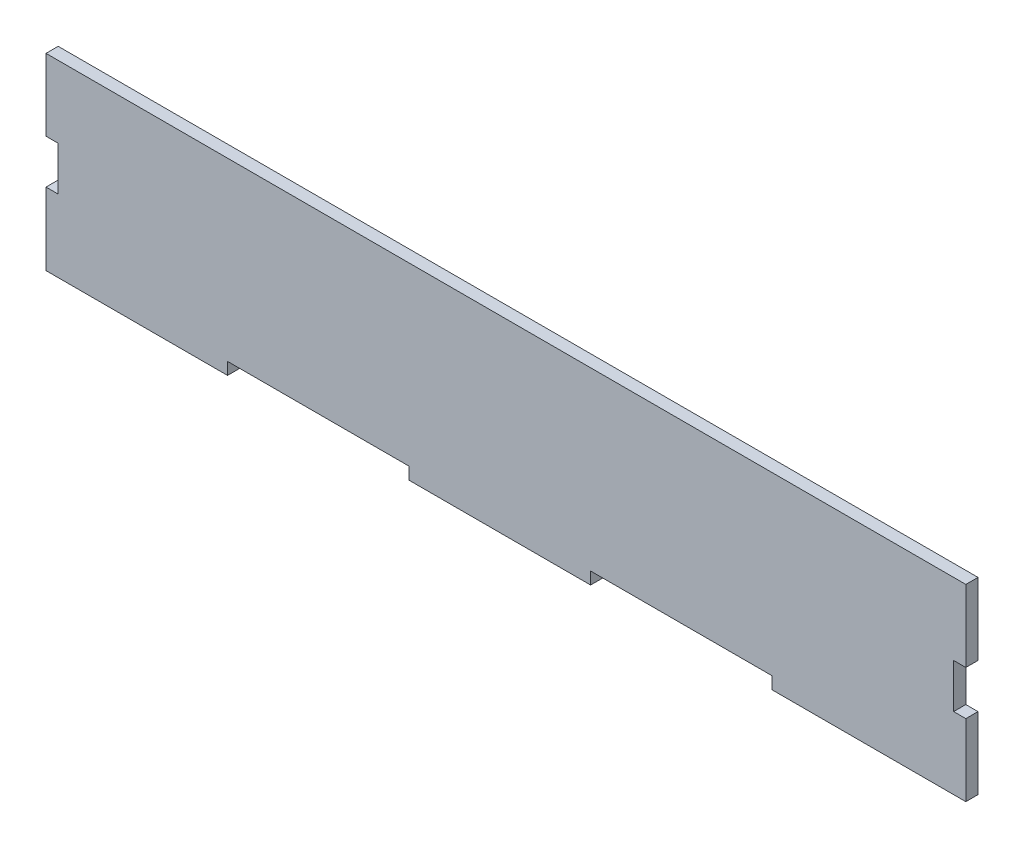
SolidWorks part; units mm, degrees
ref_plane "Alzado" through (0, 0, 0) normal (0, 0, 1) x (1, 0, 0)
ref_plane "Planta" through (0, 0, 0) normal (0, 1, 0) x (1, 0, 0)
ref_plane "Vista lateral" through (0, 0, 0) normal (1, 0, 0) x (0, 0, -1)
sketch "Croquis1" plane through (0, 0, 0) normal (0, 0, 1) x (1, 0, 0)
  line L0 (-48.5339, 1.4205) -> (-48.5339, 33.8414)
  line L1 (-48.5339, 33.8414) -> (366.9661, 33.8414)
  line L2 (-48.5339, -18.4689) -> (-48.5339, -51.1586)
  line L3 (-48.5339, -51.1586) -> (33.4661, -51.1586)
  line L4 (366.9661, 33.8414) -> (366.9661, 1.3414)
  line L5 (-48.5339, 1.4205) -> (-43.0339, 1.4205)
  line L6 (-43.0339, 1.4205) -> (-43.0339, -18.4689)
  line L7 (-43.0339, -18.4689) -> (-48.5339, -18.4689)
  line L8 (33.4661, -51.1586) -> (33.4661, -45.6586)
  line L9 (33.4661, -45.6586) -> (115.4661, -45.6586)
  line L10 (115.4661, -45.6586) -> (115.4661, -51.1586)
  line L11 (115.4661, -51.1586) -> (197.4661, -51.1586)
  line L12 (197.4661, -51.1586) -> (197.4661, -45.6586)
  line L13 (197.4661, -45.6586) -> (279.4661, -45.6586)
  line L14 (279.4661, -45.6586) -> (279.4661, -51.1586)
  line L15 (279.4661, -51.1586) -> (366.9661, -51.1586)
  line L16 (366.9661, -18.6586) -> (366.9661, -51.1586)
  line L17 (361.4661, -8.6586) -> (361.4661, 1.3414)
  line L18 (361.4661, 1.3414) -> (366.9661, 1.3414)
  line L19 (366.9661, 1.3414) -> (366.9661, -18.6586) construction
  line L20 (366.9661, -18.6586) -> (361.4661, -18.6586)
  line L21 (361.4661, -18.6586) -> (361.4661, -8.6586)
  dimension "D1" = 85
  dimension "D2" = 415.5
extrude "Saliente-Extruir1" add sketch "Croquis1" along normal blind 5.5
